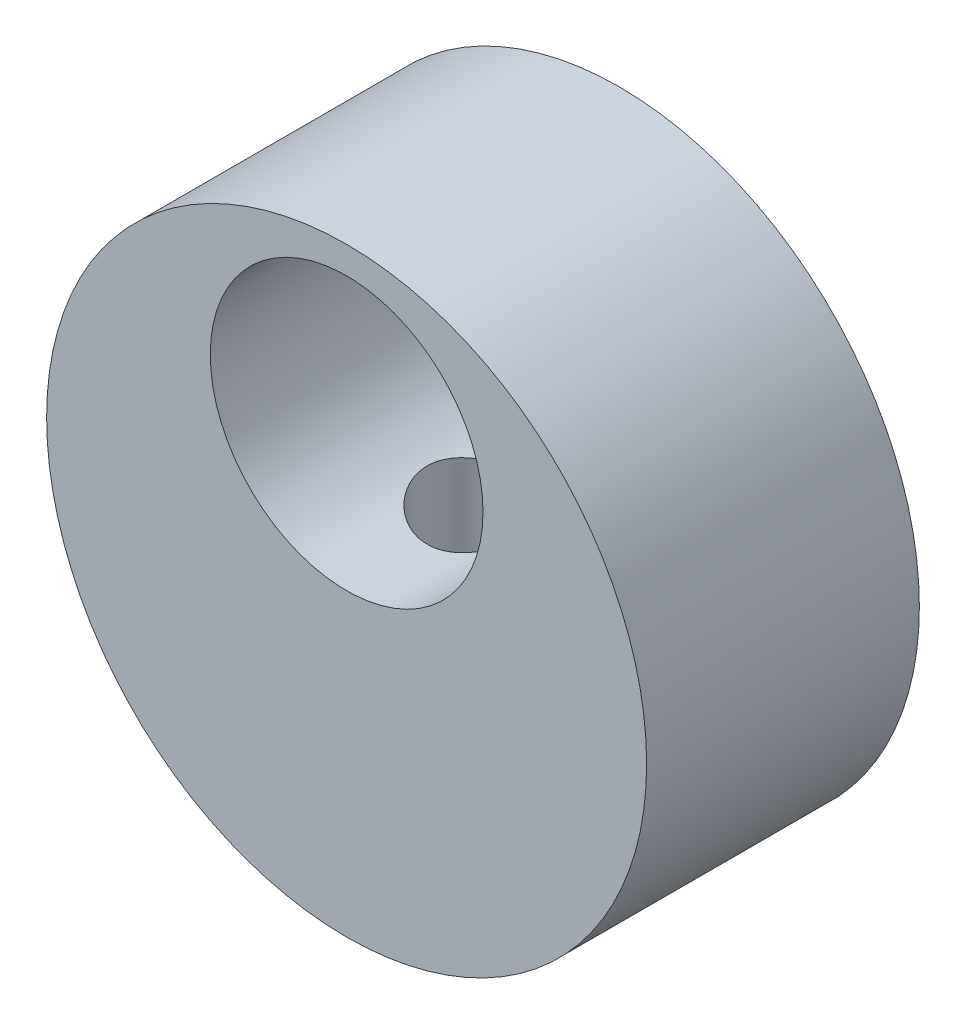
SolidWorks part; units mm, degrees
material "Gray Cast Iron"
ref_plane "Front Plane" through (0, 0, 0) normal (0, 0, 1) x (1, 0, 0)
ref_plane "Top Plane" through (0, 0, 0) normal (0, 1, 0) x (1, 0, 0)
ref_plane "Right Plane" through (0, 0, 0) normal (1, 0, 0) x (0, 0, -1)
sketch "Sketch1" plane through (0, 0, 0) normal (0, 0, 1) x (1, 0, 0)
  circle A0 centre (0, 0) radius 5.5
  dimension "D1" = 11
extrude "Boss-Extrude1" add sketch "Sketch1" along normal blind 5
ref_plane "Plane2" through (0, -5.5, 0) normal (0, -1, 0) x (-1, 0, 0)
sketch "Sketch4" plane through (0, 0, 0) normal (0, 0, -1) x (-1, 0, 0)
  circle A0 centre (0, 2.5) radius 2.5
  point P0 (0, 2.5)
  dimension "D2" = 5
  dimension "D1" = 2.5
extrude "Cut-Extrude1" cut sketch "Sketch4" against normal through all
sketch "Sketch7" plane through (0, -5.5, 0) normal (0, -1, 0) x (-1, 0, 0)
  line L0 (5.5, 0) -> (-5.5, 0) construction
  circle A0 centre (0, -2.5) radius 1.25
  point P0 (0, -2.5)
  dimension "D2" = 2.5
  dimension "D1" = 2.5
hole_wizard "M2.5 Tapped Hole2" positions "3DSketch5" profile "Sketch10" tap size "M2.5" standard "ISO" end condition up to next
sketch3d "3DSketch5"
  point P0 (0, -5.5, 2.5)
  point P3 (0, -5.5, 2.5)
  point P5 (0, -5.5, 2.5)
  point P7 (0, -5.5, 2.5)
  point P9 (0, -5.5, 2.5)
sketch "Sketch10" plane through (0, -5.5, 2.5) normal (1, 0, 0) x (0, 0, -1)
  line L0 (0, 0) -> (0, 8)
  line L1 (0, 8) -> (1.025, 8)
  line L2 (1.025, 8) -> (1.025, 0)
  line L5 (1.025, 0) -> (0, 0)
  line L11 (0, -6.35) -> (0, 107.95) construction
  dimension "Thread Major Dia." = 2.05
  dimension "Thru Tap Drill Depth" = 8
cosmetic thread "Cosmetic Thread1" parameters "D2"=2.5
